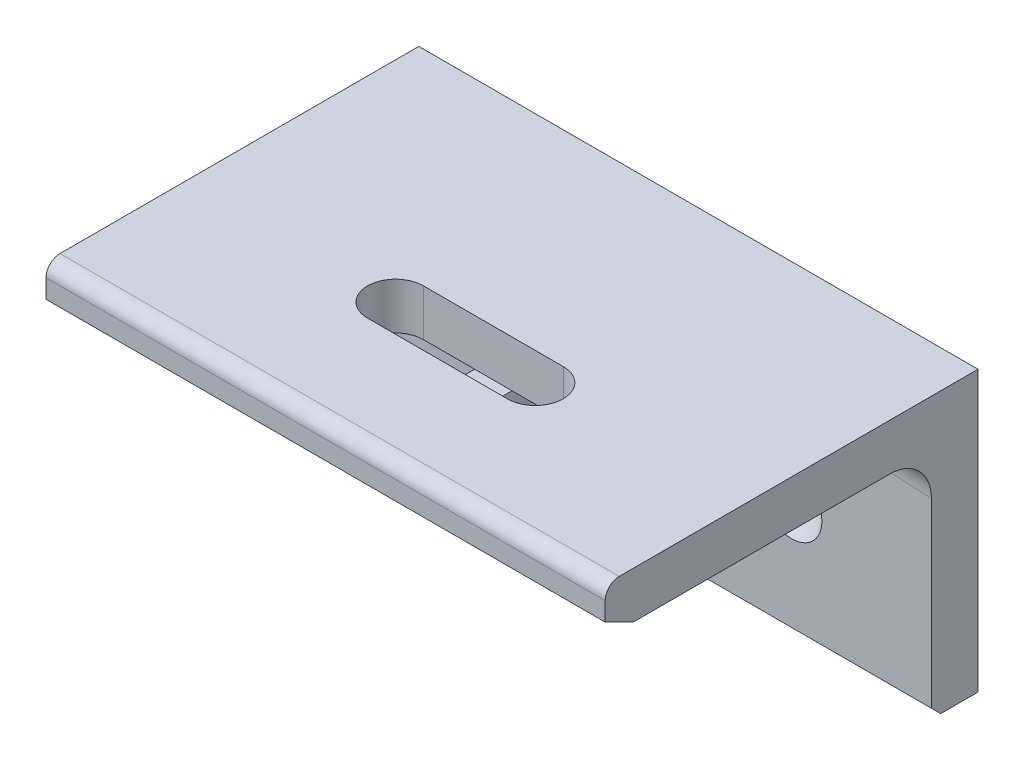
SolidWorks part; units mm, degrees
ref_plane "前视基准面" through (0, 0, 0) normal (0, 0, 1) x (1, 0, 0)
ref_plane "上视基准面" through (0, 0, 0) normal (0, 1, 0) x (1, 0, 0)
ref_plane "右视基准面" through (0, 0, 0) normal (1, 0, 0) x (0, 0, -1)
sketch "草图1" plane through (0, 0, 0) normal (1, 0, 0) x (0, 0, -1)
  line L0 (0, 0) -> (-10, 0)
  line L1 (-10, 0) -> (-10, 50)
  line L2 (-10, 50) -> (-80, 50)
  line L3 (-80, 50) -> (-80, 60)
  line L4 (-80, 60) -> (0, 60)
  line L5 (0, 60) -> (0, 0)
extrude "凸台-拉伸1" add sketch "草图1" along normal blind 120
ref_plane "基准面1" through (20, 0, 0) normal (1, 0, 0) x (0, 0, -1)
ref_plane "基准面2" through (40, 0, 0) normal (1, 0, 0) x (0, 0, -1)
ref_plane "基准面3" through (60, 0, 0) normal (1, 0, 0) x (0, 0, -1)
ref_plane "基准面4" through (80, 0, 0) normal (1, 0, 0) x (0, 0, -1)
ref_plane "基准面5" through (100, 0, 0) normal (1, 0, 0) x (0, 0, -1)
ref_plane "基准面6" through (120, 0, 0) normal (1, 0, 0) x (0, 0, -1)
sketch "草图2" plane through (0, 0, 0) normal (1, 0, 0) x (0, 0, -1)
  line L0 (-10, 47) -> (-10, 50)
  line L1 (-10, 50) -> (-13, 50)
  arc A0 (-13, 50) -> (-10, 47) centre (-13, 47) cw
sketch "草图3" plane through (20, 0, 0) normal (1, 0, 0) x (0, 0, -1)
  line L0 (-10, 46) -> (-10, 50)
  line L1 (-10, 50) -> (-14, 50)
  arc A0 (-14, 50) -> (-10, 46) centre (-14, 46) cw
sketch "草图4" plane through (40, 0, 0) normal (1, 0, 0) x (0, 0, -1)
  line L0 (-10, 45) -> (-10, 50)
  line L1 (-10, 50) -> (-15, 50)
  arc A0 (-15, 50) -> (-10, 45) centre (-14.9999, 45.0001) cw
sketch "草图5" plane through (60, 0, 0) normal (1, 0, 0) x (0, 0, -1)
  line L0 (-10, 44) -> (-10, 50)
  line L1 (-10, 50) -> (-16, 50)
  arc A0 (-16, 50) -> (-10, 44) centre (-15.9998, 44.0002) cw
sketch "草图6" plane through (80, 0, 0) normal (1, 0, 0) x (0, 0, -1)
  line L0 (-10, 43) -> (-10, 50)
  line L1 (-10, 50) -> (-17, 50)
  arc A0 (-17, 50) -> (-10, 43) centre (-16.9997, 43.0003) cw
sketch "草图7" plane through (100, 0, 0) normal (1, 0, 0) x (0, 0, -1)
  line L0 (-10, 42) -> (-10, 50)
  line L1 (-10, 50) -> (-18, 50)
  arc A0 (-18, 50) -> (-10, 42) centre (-17.9996, 42.0004) cw
sketch "草图8" plane through (120, 0, 0) normal (1, 0, 0) x (0, 0, -1)
  line L0 (-10, 41) -> (-10, 50)
  line L1 (-10, 50) -> (-19, 50)
  arc A0 (-19, 50) -> (-10, 41) centre (-18.9995, 41.0005) cw
loft "放样1" add profiles "草图2", "草图3", "草图4", "草图5", "草图6", "草图7", "草图8"
ref_plane "基准面7" through (56, 0, 0) normal (1, 0, 0) x (0, 0, -1)
sketch "草图9" plane through (56, 0, 0) normal (1, 0, 0) x (0, 0, -1)
  line L0 (-10, 50) -> (-10, 10)
  line L1 (-10, 10) -> (-60, 50)
  line L2 (-60, 50) -> (-10, 50)
extrude "凸台-拉伸2" add sketch "草图9" along normal blind 8
sketch "草图10" plane through (0, 0, 0) normal (1, 0, 0) x (0, 0, -1)
  line L0 (-80, 50) -> (-80, 53)
  line L1 (-80, 53) -> (-74, 50)
  line L2 (-74, 50) -> (-80, 50)
extrude "切除-拉伸1" cut sketch "草图10" along normal blind 120
fillet "圆角1" radius 3 1 edges at (60, 60, 80)
chamfer "倒角1" distance 2 angle 45 1 edges at (60, 0, 10)
ref_plane "基准面8" through (0, 0, 10) normal (0, 0, 1) x (1, 0, 0)
sketch "草图11" plane through (0, 0, 10) normal (0, 0, 1) x (1, 0, 0)
  circle A0 centre (30, 25) radius 6.5
  circle A1 centre (90, 25) radius 6.5
extrude "切除-拉伸2" cut sketch "草图11" against normal blind 3.2 draft 45
sketch "草图12" plane through (0, 0, 10) normal (0, 0, 1) x (1, 0, 0)
  circle A0 centre (30, 25) radius 3.3
  circle A1 centre (90, 25) radius 3.3
extrude "切除-拉伸3" cut sketch "草图12" against normal through all
ref_plane "基准面9" through (0, 48, 0) normal (0, 1, 0) x (1, 0, 0)
ref_plane "基准面10" through (0, 50, 0) normal (0, 1, 0) x (1, 0, 0)
sketch "草图14" plane through (0, 50, 0) normal (0, 1, 0) x (1, 0, 0)
  line L0 (45, -44) -> (75, -44)
  line L1 (75, -56) -> (45, -56)
  arc A0 (75, -44) -> (75, -56) centre (75, -50) cw
  arc A1 (45, -56) -> (45, -44) centre (45, -50) cw
extrude "切除-拉伸5" cut sketch "草图14" along normal through all
